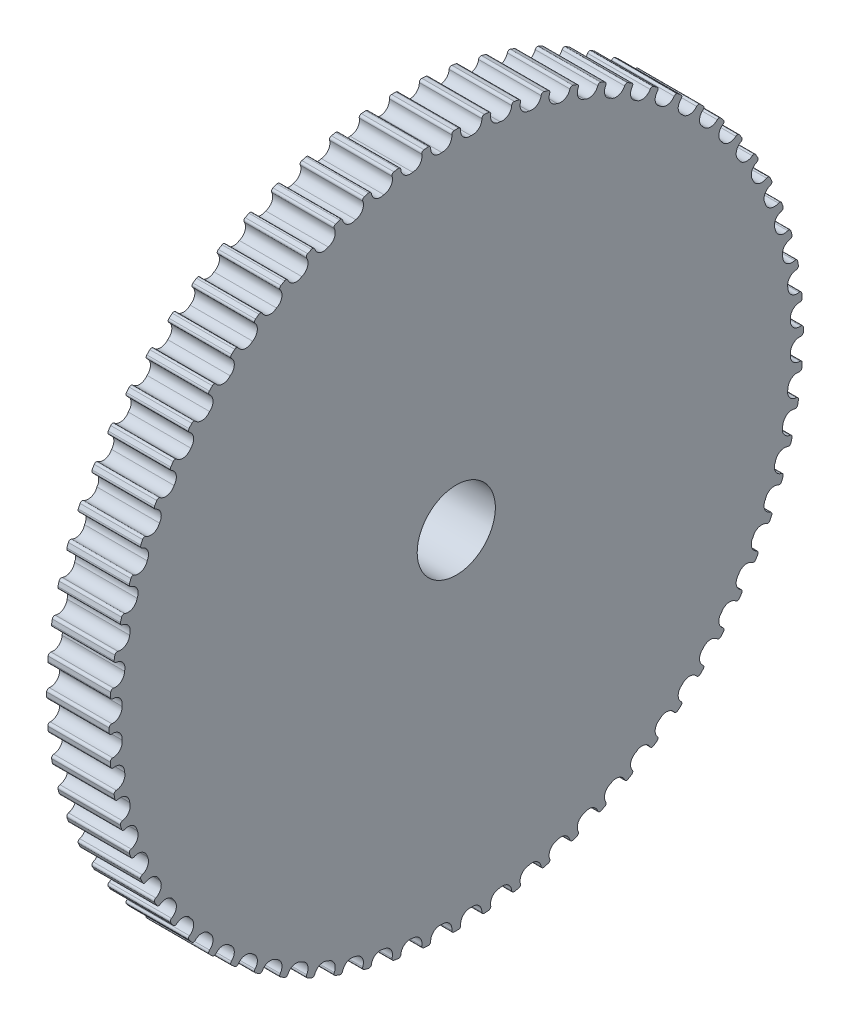
SolidWorks part; units mm, degrees
ref_plane "Front Plane" through (0, 0, 0) normal (0, 0, 1) x (1, 0, 0)
ref_plane "Top Plane" through (0, 0, 0) normal (0, 1, 0) x (1, 0, 0)
ref_plane "Right Plane" through (0, 0, 0) normal (1, 0, 0) x (0, 0, -1)
sketch "Sketch3" plane through (0, 0, 0) normal (1, 0, 0) x (0, 0, -1)
  circle A0 centre (0, 0) radius 57.277
  dimension "D1" = 114.554
extrude "Boss-Extrude1" add sketch "Sketch3" along normal blind 10.16 separate body contours A0
sketch "Sketch4" plane through (0, 0, 0) normal (-1, 0, 0) x (0, 0, 1)
  circle A0 centre (0, 0) radius 6.35
  dimension "D1" = 12.7
sketch "Sketch5" plane through (0, 0, 0) normal (-1, 0, 0) x (0, 0, 1)
  line L1 (0, 0) -> (0, 55.7787) construction
  line L2 (0, 0) -> (2.5061, 57.398) construction
  line L3 (-0.0339, 56.4053) -> (0.3471, 56.4053)
  line L4 (-0.0339, 56.4053) -> (-0.0339, 57.3284)
  line L5 (-0.0339, 57.3284) -> (2.5061, 57.398)
  line L6 (5.0303, 57.1073) -> (2.5061, 57.398)
  line L7 (4.9499, 56.1877) -> (5.0303, 57.1073)
  line L8 (4.9499, 56.1877) -> (4.5703, 56.2209)
  arc A0 (0.3471, 56.4053) -> (0.7255, 55.9802) centre (0.3471, 56.0243) cw
  arc A1 (0.7255, 55.9802) -> (2.372, 54.3271) centre (2.2055, 55.8077) ccw
  arc A2 (4.1563, 55.8304) -> (2.372, 54.3271) centre (2.6669, 55.7876) cw
  arc A3 (4.5703, 56.2209) -> (4.1563, 55.8304) centre (4.5371, 55.8414) ccw
  dimension "D1" = 0.381
  dimension "D2" = 1.49
  dimension "D3" = 0.9231
  dimension "D4" = 3.0013
  dimension "D5" = 2.5
  dimension "D6" = 0.381
  dimension "D7" = 2.54
extrude "Cut-Extrude4" cut sketch "Sketch5" against normal through all contours L5 L6 L7 L8 A3 A2 A1 A0 L3 L4
pattern_circular "CirPattern1" count 72 over 360 about axis through (0, 0, 0) along (1, 0, 0) of "Cut-Extrude4"
extrude "Cut-Extrude5" cut sketch "Sketch4" against normal through all both and the other way through all contours A0
equation "\"z\"= 72'INPUT: number of teeth"
equation "\"p\"= 5mm'INPUT: pitch (inches)"
equation "\"D_b\"= 1.25'INPUT: bore diameter (inches)"
equation "\"s\"= 0.5'INPUT: face width (inches)"
equation "\"D_p\"= \"z\" * \"p\" / pi'pitch circle diameter"
equation "\"theta\"= 180 / \"z\"'tooth angular size half (degrees)"
